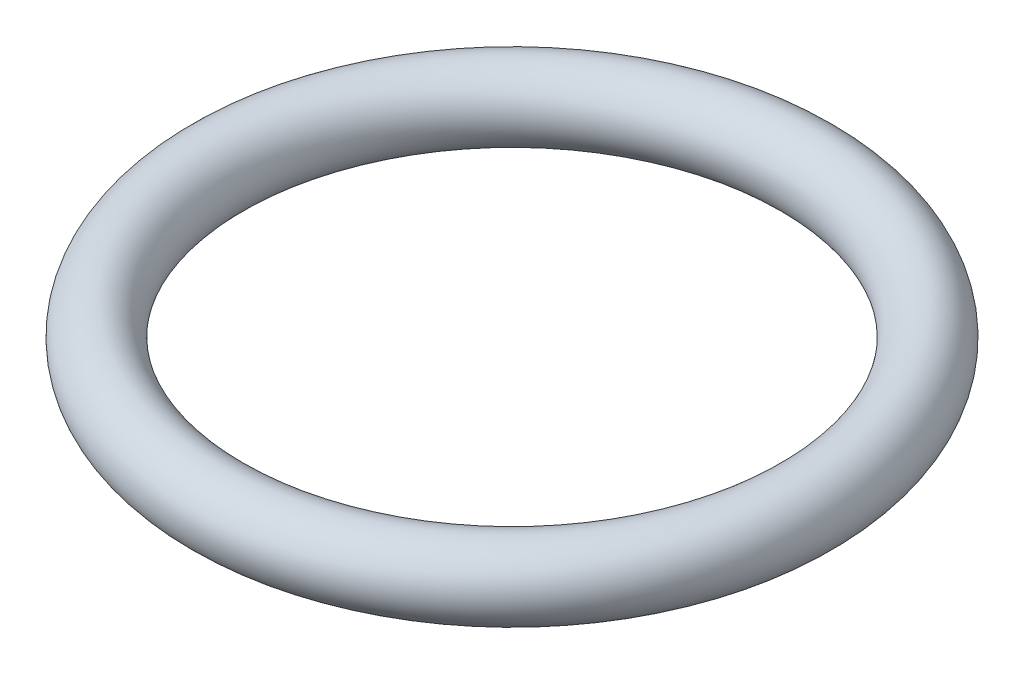
SolidWorks part; units mm, degrees
ref_plane "Front Plane" through (0, 0, 0) normal (0, 0, 1) x (1, 0, 0)
ref_plane "Top Plane" through (0, 0, 0) normal (0, 1, 0) x (1, 0, 0)
ref_plane "Right Plane" through (0, 0, 0) normal (1, 0, 0) x (0, 0, -1)
sketch "Reconstructed nominal axial profile" plane through (0, 0, 0) normal (0, 0, 1) x (1, 0, 0)
  line L0 (0, -500) -> (0, 50) construction
  circle A0 centre (8.25, 0) radius 1
revolve "Native revolved geometry" add sketch "Reconstructed nominal axial profile" angle 360 about L0
